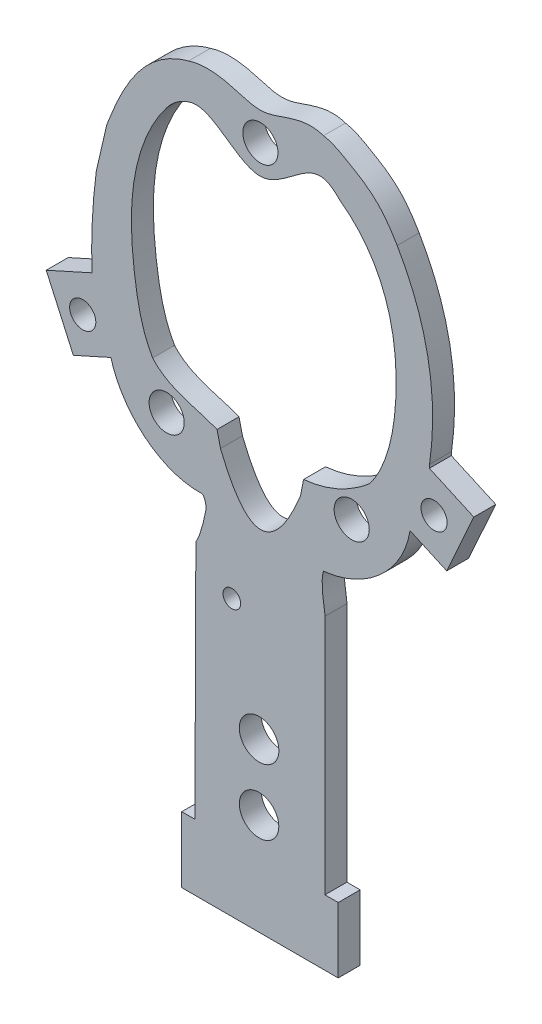
SolidWorks part; units mm, degrees
ref_plane "Front Plane" through (0, 0, 0) normal (0, 0, 1) x (1, 0, 0)
ref_plane "Top Plane" through (0, 0, 0) normal (0, 1, 0) x (1, 0, 0)
ref_plane "Right Plane" through (0, 0, 0) normal (1, 0, 0) x (0, 0, -1)
sketch "Sketch1" plane through (0, 0, 0) normal (0, 0, 1) x (1, 0, 0)
  line L0 (-9.7409, -2.7228) -> (-7.6559, -1.7839)
  line L1 (-9.7409, -2.7228) -> (-8.507, -5.4628)
  line L2 (-6.7979, -4.6932) -> (-8.507, -5.4628)
  line L3 (-2.9271, -10.0287) -> (-2.9689, -20.9936)
  line L4 (8.4984, -5.4628) -> (6.8268, -4.7101)
  line L5 (0.9972, -4.1898) -> (2.9211, -7.9433) construction
  line L6 (-1.804, -5.788) -> (-1.9624, -5.1145)
  line L7 (-2.9689, -20.9936) -> (-3.5693, -20.9936)
  line L9 (-3.5693, -20.9936) -> (-3.5693, -23.9903)
  line L10 (-3.5693, -23.9903) -> (3.5569, -23.9903)
  line L11 (2.9522, -10.0287) -> (2.9522, -21.0127)
  line L12 (2.9522, -21.0127) -> (3.5569, -21.0127)
  line L13 (3.5569, -21.0127) -> (3.5569, -23.9903)
  line L14 (8.4984, -5.4628) -> (9.7323, -2.7228)
  line L15 (7.7078, -1.8111) -> (9.7323, -2.7228)
  circle A0 centre (0.0128, 7.1829) radius 0.8
  circle A1 centre (-4.2565, -5.5977) radius 0.8
  circle A2 centre (4.1707, -5.5977) radius 0.8
  parabola Q1 (-1.804, -5.788) -> (1.8395, -5.833) focus (0.0291, -7.7022) apex (0.0294, -8.0695)
  spline S0 degree 2 poles (-7.46, 2.3295) (-7.7307, 0.2801) (-7.6559, -1.7839) knots 0 0 0 1 1 1
  spline S1 degree 1 poles (1.8395, -5.833) (1.9799, -5.1145) knots 0 0 1 1
  spline S2 degree 2 poles (6.2427, 6.2435) (8.3285, 2.6572) (7.7171, -1.6493) knots 0 0 0 1 1 1
  spline S3 degree 1 poles (-6.9783, 4.4185) (-7.46, 2.3295) knots 0 0 1 1
  spline S5 degree 2 poles (-3.2618, 7.1574) (-3.8718, 6.9419) (-4.2565, 6.4244) knots 0 0 0 1 1 1
  spline S6 degree 3 poles (1.9799, -5.1145) (3.1025, -5.0178) (4.1627, -4.4994) (5.0056, -3.7616) knots 0 0 0 0 1 1 1 1
  spline S7 degree 3 poles (6.8268, -4.7101) (6.5307, -6.6075) (4.7615, -8.1039) (2.8857, -8.2732) knots 0 0 0 0 1 1 1 1
  spline S8 degree 3 poles (-2.6193, -7.991) (-4.5889, -8.0615) (-6.2914, -6.5102) (-6.7979, -4.6932) knots 0 0 0 0 1 1 1 1
  spline S9 degree 3 poles (2.8886, 8.8962) (2.2803, 9.1021) (1.336, 8.8332) (-0.0213, 8.3193) (-1.4672, 8.8658) (-2.5953, 8.9907) (-3.2618, 8.769) knots 0 0 0 0 0.291998 0.463731 0.671653 1 1 1 1
  spline S10 degree 3 poles (-1.9624, -5.1145) (-2.9417, -4.7148) (-4.1534, -4.6145) (-4.8956, -3.7616) knots 0 0 0 0 1 1 1 1
  spline S15 degree 2 poles (-2.4609, -8.4961) (-2.6549, -9.5597) (-2.9271, -10.0287) knots 0.505401 0.505401 0.505401 1 1 1
  spline S28 degree 2 poles (-2.6193, -7.991) (-2.4655, -8.1867) (-2.4609, -8.4961) knots 0.760656 0.760656 0.760656 1 1 1
  spline S30 degree 1 poles (7.7171, -1.6493) (7.7078, -1.8111) knots 0 0 1 1
  spline S32 degree 3 poles (-4.2565, 6.4244) (-5.0248, 5.4358) (-5.9871, 2.9608) (-5.8493, -0.5681) (-5.3759, -2.947) (-4.8956, -3.7616) knots 0 0 0 0 0.272446 0.55607 0.771313 0.771313 0.771313 0.771313
  spline S34 degree 3 poles (-6.9783, 4.4185) (-6.9783, 4.4186) (-6.2458, 6.3079) (-5.3173, 8.2885) (-3.1246, 8.8036) knots 0.18371 0.18371 0.18371 0.18371 0.18372 1 1 1 1
  spline S35 degree 3 poles (2.9522, -10.0287) (2.9534, -9.7303) (2.7158, -8.8482) (2.8857, -8.2732) knots 0 0 0 0 0.672395 0.672395 0.672395 0.672395
  spline S36 degree 3 poles (2.8886, 8.8962) (2.9852, 8.8795) (3.2478, 8.8086) (3.6301, 8.6426) (4.0742, 8.3687) (4.7219, 8.01) (5.5502, 7.346) (6.0129, 6.6331) (6.2427, 6.2435) (6.2427, 6.2435) knots 0.68012 0.68012 0.68012 0.68012 0.700211 0.734682 0.764415 0.805838 0.88492 0.976406 0.976409 0.976409 0.976409 0.976409
  spline S40 degree 3 poles (-3.2618, 7.1574) (-3.163, 7.19) (-2.1174, 7.4106) (0.0771, 4.3901) (2.2474, 7.8099) (3.3703, 6.9888) (3.5935, 6.757) knots 0.22367 0.22367 0.22367 0.22367 0.25032 0.504381 0.763196 0.835276 0.835276 0.835276 0.835276
  spline S41 degree 3 poles (3.5935, 6.757) (5.6442, 5.2681) (6.6508, 1.422) (5.8318, -2.644) (5.0056, -3.7616) knots 0 0 0 0 0.480405 0.775339 0.775339 0.775339 0.775339
extrude "Boss-Extrude1" add sketch "Sketch1" along normal blind 1 from offset 1 offset against normal yes
sketch3d "3DSketch7"
  line L7 (2.9522, -21.0127, -1) -> (2.9522, -10.0287, -1)
  line L8 (3.5569, -21.0127, -1) -> (2.9522, -21.0127, -1)
  line L9 (3.5569, -23.9903, -1) -> (3.5569, -21.0127, -1)
  line L10 (-3.5693, -23.9903, -1) -> (3.5569, -23.9903, -1)
  line L11 (-3.5693, -20.9936, -1) -> (-3.5693, -23.9903, -1)
  line L12 (-2.9689, -20.9936, -1) -> (-3.5693, -20.9936, -1)
  line L13 (-2.9271, -10.0287, -1) -> (-2.9689, -20.9936, -1)
  line L14 (2.9522, -21.0127, -1) -> (2.9522, -10.0287, -1)
  line L15 (3.5569, -21.0127, -1) -> (2.9522, -21.0127, -1)
  line L16 (3.5569, -23.9903, -1) -> (3.5569, -21.0127, -1)
  line L17 (-3.5693, -23.9903, -1) -> (3.5569, -23.9903, -1)
  line L18 (-3.5693, -20.9936, -1) -> (-3.5693, -23.9903, -1)
  line L19 (-2.9689, -20.9936, -1) -> (-3.5693, -20.9936, -1)
  line L20 (-2.9271, -10.0287, -1) -> (-2.9689, -20.9936, -1)
  line L27 (9.7323, -2.7228, -1) -> (7.7078, -1.8111, -1)
  line L28 (9.7323, -2.7228, -1) -> (7.7078, -1.8111, -1)
  line L29 (8.4984, -5.4628, -1) -> (9.7323, -2.7228, -1)
  line L30 (8.4984, -5.4628, -1) -> (9.7323, -2.7228, -1)
  line L31 (7.7078, -1.8111, -1) -> (7.7171, -1.6493, -1)
  line L32 (7.7078, -1.8111, -1) -> (7.7171, -1.6493, -1)
  line L33 (-8.507, -5.4628, -1) -> (-6.3065, -4.4718, -1)
  line L34 (-8.507, -5.4628, -1) -> (-6.3065, -4.4718, -1)
  line L35 (-9.7409, -2.7228, -1) -> (-8.507, -5.4628, -1)
  line L36 (-9.7409, -2.7228, -1) -> (-8.507, -5.4628, -1)
  line L37 (-7.6559, -1.7839, -1) -> (-9.7409, -2.7228, -1)
  line L38 (-7.6559, -1.7839, -1) -> (-9.7409, -2.7228, -1)
  line L41 (6.488, -4.5575, -1) -> (8.4984, -5.4628, -1)
  line L42 (6.488, -4.5575, -1) -> (8.4984, -5.4628, -1)
  circle A0 centre (-0.047, -16.3763, 0) radius 0.9008
  arc A1 (-7.0304, 3.619, -1) -> (-7.2614, 2.994, -1) centre (2.8251, -0.3797, -1) ccw
  arc A2 (-7.0304, 3.619, -1) -> (-7.2614, 2.994, -1) centre (2.8251, -0.3797, -1) ccw
  circle A4 centre (-0.0474, -19.368, 0) radius 0.8985
  arc A7 (-3.7026, -7.2722, -1) -> (-3.5693, -7.3644, -1) centre (1.4394, 0.0183, -1) ccw
  arc A8 (-3.7026, -7.2722, -1) -> (-3.5693, -7.3644, -1) centre (1.4394, 0.0183, -1) ccw
  arc A9 (4.0353, -7.2745, -1) -> (4.0925, -7.234, -1) centre (8.2948, -13.2428, -1) ccw
  arc A10 (4.0353, -7.2745, -1) -> (4.0925, -7.234, -1) centre (8.2948, -13.2428, -1) ccw
  spline S7 degree 3 poles (16245.8482, -22785.9689, -1) (147.3264, 151.5836, -1) (2.2469, 43.5464, -1) (-8.8485, -2.0938, -1) (10117.4407, 26051.7404, -0.8698) knots -19.056934 -19.056934 -19.056934 -19.056934 0.999991 2.282833 2.282833 2.282833 2.282833 only from (-3.1766, 8.004, -1) to (-7.0304, 3.619, -1)
  spline S8 degree 3 poles (-14197.2158, 24088.353, -1.5765) (7.9336, 1.6566, -1) (7.1166, 4.0529, -1) (5.4982, 6.5465, -1) (4.6699, 7.2105, -1) (4.0222, 7.5691, -1) (3.5781, 7.843, -1) (3.1958, 8.0091, -1) (2.1082, 8.3028, -1) (1.0772, 7.6211, -1) (-0.0788, 7.5899, -1) (-0.8646, 7.6691, -1) (-1.7745, 7.9381, -1) (-18.6429, 9.032, -1) (-34.9505, -3.3358, -1) (222.8613, -27986.7939, -1) knots -0.157748 -0.157748 -0.157748 -0.157748 0.268305 0.359791 0.438874 0.480296 0.51003 0.5445 0.564591 0.736043 0.759616 0.798759 0.895631 0.950635 4.217339 4.217339 4.217339 4.217339 only from (6.1907, 5.4439, -1) to (-3.1766, 8.004, -1)
  spline S9 degree 2 poles (-26178.8241, -9872.7187, -1) (26459.7481, 9103.1578, -1) (-26712.3664, -8319.7462, -1) knots -113.270233 -113.270233 -113.270233 114.670111 114.670111 114.670111 only from (7.7171, -1.6493, -1) to (6.1907, 5.4439, -1)
  spline S10 degree 3 poles (22100.2262, 17166.8643, -1) (-22172.1406, -17143.4803, -1) (22170.6934, 17121.9183, -1) (-22121.8326, -17162.5714, -1) knots -29.318845 -29.318845 -29.318845 -29.318845 29.754948 29.754948 29.754948 29.754948 only from (-3.5693, -7.3644, -1) to (-2.4609, -8.4961, -1)
  spline S11 degree 1 poles (5577.7052, -27436.747, -1) (-5593.0721, 27433.4498, -1) knots -179999.143591 -179999.143591 180000.917962 180000.917962 only from (-7.6559, -1.7839, -1) to (-7.687, -1.6314, -1)
  spline S12 degree 3 poles (-10488.1696, -25933.2421, -1) (11923.797, 25532.5645, -1) (-13289.5194, -24843.9465, -1) (14527.8459, 23893.0729, -1) knots -11.726885 -11.726885 -11.726885 -11.726885 12.198194 12.198194 12.198194 12.198194 only from (-7.46, 2.3296, -1) to (-7.687, -1.6314, -1)
  spline S13 degree 3 poles (-21277.6435, 18197.8517, -1) (21421.2708, -17926.2556, -1) (-21536.0534, 17815.099, -1) (21566.1237, -17834.4648, -1) knots -168.174273 -168.174273 -168.174273 -168.174273 165.883512 165.883512 165.883512 165.883512 only from (-7.2614, 2.994, -1) to (-7.46, 2.3296, -1)
  spline S14 degree 3 poles (-3.1766, 8.004, -1) (-5.3693, 7.4889, -1) (-6.2978, 5.5083, -1) (-7.0303, 3.619, -1) (-7.0304, 3.619, -1) knots 0.18371 0.18371 0.18371 0.18371 0.999991 1 1 1 1
  spline S15 degree 3 poles (6.1907, 5.4439, -1) (6.1907, 5.4439, -1) (5.9609, 5.8336, -1) (5.4982, 6.5465, -1) (4.6699, 7.2105, -1) (4.0222, 7.5691, -1) (3.5781, 7.843, -1) (3.1958, 8.0091, -1) (2.1082, 8.3028, -1) (1.0772, 7.6211, -1) (-0.0788, 7.5899, -1) (-0.8646, 7.6691, -1) (-1.7745, 7.9381, -1) (-2.6511, 7.995, -1) (-3.0496, 8.0129, -1) (-3.1766, 8.004, -1) knots 0.268303 0.268303 0.268303 0.268303 0.268305 0.359791 0.438874 0.480296 0.51003 0.5445 0.564591 0.736043 0.759616 0.798759 0.895631 0.950635 0.976409 0.976409 0.976409 0.976409
  spline S16 degree 2 poles (7.7171, -1.6493, -1) (7.9722, 2.2476, -1) (6.1907, 5.4439, -1) knots 0 0 0 1 1 1
  spline S17 degree 3 poles (-3.5693, -7.3644, -1) (-3.0978, -7.6687, -1) (-2.4417, -7.8242, -1) (-2.4609, -8.4961, -1) knots 0 0 0 0 1 1 1 1
  spline S18 degree 1 poles (-7.6559, -1.7839, -1) (-7.687, -1.6314, -1) knots 0 0 1 1
  spline S19 degree 3 poles (-7.46, 2.3296, -1) (-7.8009, 1.0369, -1) (-7.9017, -0.3336, -1) (-7.687, -1.6314, -1) knots 0.285802 0.285802 0.285802 0.285802 0.503018 0.503018 0.503018 0.503018
  spline S20 degree 3 poles (-7.2614, 2.994, -1) (-7.3362, 2.7761, -1) (-7.4039, 2.5559, -1) (-7.46, 2.3296, -1) knots 0 0 0 0 1 1 1 1
  spline S23 degree 2 poles (-3505.759, 27767.0237, -1) (3640.6801, -27768.2572, -1) (-3789.0194, 27727.9101, -1) knots -105.510296 -105.510296 -105.510296 108.215215 108.215215 108.215215 only from (-2.4609, -8.4961, -1) to (-2.9271, -10.0287, -1)
  spline S24 degree 2 poles (-2.4609, -8.4961, -1) (-2.6549, -9.5597, -1) (-2.9271, -10.0287, -1) knots 0.505401 0.505401 0.505401 1 1 1
  spline S25 degree 3 poles (-23383.7193, -15401.6247, -1) (23315.9779, 15441.8882, -1) (-23311.4556, -15474.8144, -1) (23339.7372, 15442.817, -1) knots -20.40459 -20.40459 -20.40459 -20.40459 20.637457 20.637457 20.637457 20.637457 only from (-4.0111, -7.0465, -1) to (-3.7026, -7.2722, -1)
  spline S26 degree 3 poles (-4.0111, -7.0465, -1) (-3.9031, -7.1192, -1) (-3.8049, -7.1976, -1) (-3.7026, -7.2722, -1) knots 0 0 0 0 0.172847 0.172847 0.172847 0.172847
  spline S33 degree 3 poles (24157.1201, 14119.3686, -1) (117.1414, 141.0981, -1) (-21.5579, 13.7548, -1) (-5.3714, -5.8792, -1) (-4.9653, -6.2932, -1) (27.166, -31.9728, -1) (82.5259, -32.9693, -1) (15559.8304, 23261.3799, -1) knots -14.974358 -14.974358 -14.974358 -14.974358 0.233209 0.27388 0.520529 0.584263 25.332128 25.332128 25.332128 25.332128 only from (-5.9856, -5.0693, -1) to (-4.0111, -7.0465, -1)
  spline S34 degree 3 poles (-5.9856, -5.0693, -1) (-5.9052, -5.2073, -1) (-5.7735, -5.3914, -1) (-5.3714, -5.8792, -1) (-4.9653, -6.2932, -1) (-4.4107, -6.7364, -1) (-4.171, -6.9256, -1) (-4.0111, -7.0465, -1) knots 0.135595 0.135595 0.135595 0.135595 0.233209 0.27388 0.520529 0.584263 0.706412 0.706412 0.706412 0.706412
  spline S35 degree 3 poles (26513.6598, 8953.4413, -1) (58.8238, 72.893, -1) (-118.06, -80.9998, -1) (180.7794, 54.7551, -1) (-23940.3747, -14522.9208, -1) knots -71.371246 -71.371246 -71.371246 -71.371246 0.499736 102.892217 102.892217 102.892217 102.892217 only from (-6.3065, -4.4718, -1) to (-5.9856, -5.0693, -1)
  spline S36 degree 3 poles (-6.3065, -4.4718, -1) (-6.2678, -4.5783, -1) (-6.1647, -4.7807, -1) (-6.0461, -4.9735, -1) (-5.9856, -5.0693, -1) knots 0 0 0 0 0.499736 1 1 1 1
  spline S37 degree 3 poles (27941.3505, -1777.1304, -1) (-496.0098, 257.4486, -1) (328.7652, -254.2269, -1) (-198.7089, 216.6121, -1) (22632.7223, -16485.5797, -1) knots -54.581279 -54.581279 -54.581279 -54.581279 0.316826 40.437846 40.437846 40.437846 40.437846 only from (5.1698, -6.3607, -1) to (6.488, -4.5575, -1)
  spline S38 degree 3 poles (5.1698, -6.3607, -1) (5.3393, -6.1954, -1) (5.8445, -5.6407, -1) (6.2, -4.9772, -1) (6.488, -4.5575, -1) knots 0 0 0 0 0.316826 1 1 1 1
  spline S39 degree 3 poles (-17171.269, 22098.1981, -1) (17110.1562, -22178.6034, -1) (-17102.9631, 22163.2837, -1) (17190.4728, -22103.6659, -1) knots -14.86094 -14.86094 -14.86094 -14.86094 15.235223 15.235223 15.235223 15.235223 only from (5.0056, -6.5152, -1) to (5.1698, -6.3607, -1)
  spline S40 degree 3 poles (5.0056, -6.5152, -1) (5.0604, -6.4638, -1) (5.115, -6.4122, -1) (5.1698, -6.3607, -1) knots 0.162232 0.162232 0.162232 0.162232 0.206539 0.206539 0.206539 0.206539
  spline S41 degree 3 poles (9203.1331, -26441.8548, -1) (-9549.0882, 26255.1931, -1) (9767.7008, -26195.4271, -1) (-9829.8221, 26202.2012, -1) knots -108.092912 -108.092912 -108.092912 -108.092912 107.171666 107.171666 107.171666 107.171666 only from (4.0925, -7.234, -1) to (5.0056, -6.5152, -1)
  spline S42 degree 3 poles (4.0925, -7.234, -1) (4.4121, -7.0079, -1) (4.719, -6.7753, -1) (5.0056, -6.5152, -1) knots 0 0 0 0 1 1 1 1
  spline S43 degree 3 poles (17250.2894, -22058.1806, -1) (-17319.4711, 21996.1966, -1) (17323.7934, -22013.069, -1) (-17232.5787, 22049.6064, -1) knots -36.417999 -36.417999 -36.417999 -36.417999 38.168482 38.168482 38.168482 38.168482 only from (3.0262, -7.991, -1) to (4.0353, -7.2745, -1)
  spline S44 degree 3 poles (3.0262, -7.991, -1) (3.3167, -7.6948, -1) (3.6848, -7.4962, -1) (4.0353, -7.2745, -1) knots 0.341943 0.341943 0.341943 0.341943 1 1 1 1
  spline S45 degree 3 poles (-16142.4116, 22856.729, -1) (16364.8807, -22801.6269, -1) (-16568.3872, 22630.8449, -1) (16775.6811, -22417.5192, -1) knots -19.411099 -19.411099 -19.411099 -19.411099 20.15928 20.15928 20.15928 20.15928 only from (2.9522, -10.0287, -1) to (3.0262, -7.991, -1)
  spline S46 degree 3 poles (2.9522, -10.0287, -1) (2.9536, -9.675, -1) (2.6195, -8.5013, -1) (3.0262, -7.991, -1) knots 0 0 0 0 0.796954 0.796954 0.796954 0.796954
  point P4 (1.4394, 0.0183, 7.9214)
  point P13 (1.4394, 0.0183, 7.9214)
  point P17 (2.8251, -0.3797, 9.6357)
  point P19 (2.8251, -0.3797, 9.6357)
  point P21 (-0.047, -16.3763, 0.9008)
  point P23 (8.2948, -13.2428, -8.3324)
  point P24 (8.2948, -13.2428, -8.3324)
  point P28 (-0.0474, -19.368, 0.8985)
  dimension "D1" = 0
sketch "Sketch7" plane through (0, 0, 0) normal (0, 0, 1) x (1, 0, 0)
  circle A0 centre (-0.0474, -19.368) radius 0.8985 construction
  circle A1 centre (-0.047, -16.3763) radius 0.9008 construction
  circle A2 centre (-0.0474, -19.368) radius 0.8985
  circle A3 centre (-0.047, -16.3763) radius 0.9008
  circle A4 centre (-1.2873, -11.4464) radius 0.4023
extrude "Cut-Extrude9" cut sketch "Sketch7" against normal blind 10
hole_wizard "#0-80 Tapped Hole2" positions "Sketch9" profile "Sketch8" tap size "#0-80" standard "ANSI Inch" end condition through all
sketch "Sketch9" plane through (0, 0, -1) normal (0, 0, -1) x (-1, 0, 0)
  point P0 (-7.9227, -3.557)
sketch "Sketch8" plane through (7.9227, -3.557, -1) normal (1, 0, 0) x (0, 1, 0)
  line L0 (0, 0) -> (0, 1)
  line L1 (0, 1) -> (0.5956, 1)
  line L2 (0.5956, 1) -> (0.5956, 0)
  line L5 (0.5956, 0) -> (0, 0)
  line L11 (0, -6.35) -> (0, 107.95) construction
  dimension "Thru Tap Drill Dia." = 1.1913
  dimension "Thru Tap Drill Depth" = 1
cosmetic thread "Hole Thread4" parameters "D2"=1.524
hole_wizard "#0-80 Tapped Hole3" positions "Sketch11" profile "Sketch10" tap size "#0-80" standard "ANSI Inch" end condition through all
sketch "Sketch11" plane through (0, 0, -1) normal (0, 0, -1) x (-1, 0, 0)
  point P0 (8.079, -3.6451)
sketch "Sketch10" plane through (-8.079, -3.6451, -1) normal (1, 0, 0) x (0, 1, 0)
  line L0 (0, 0) -> (0, 1)
  line L1 (0, 1) -> (0.5956, 1)
  line L2 (0.5956, 1) -> (0.5956, 0)
  line L5 (0.5956, 0) -> (0, 0)
  line L11 (0, -6.35) -> (0, 107.95) construction
  dimension "Thru Tap Drill Dia." = 1.1913
  dimension "Thru Tap Drill Depth" = 1
cosmetic thread "Hole Thread5" parameters "D2"=1.524
